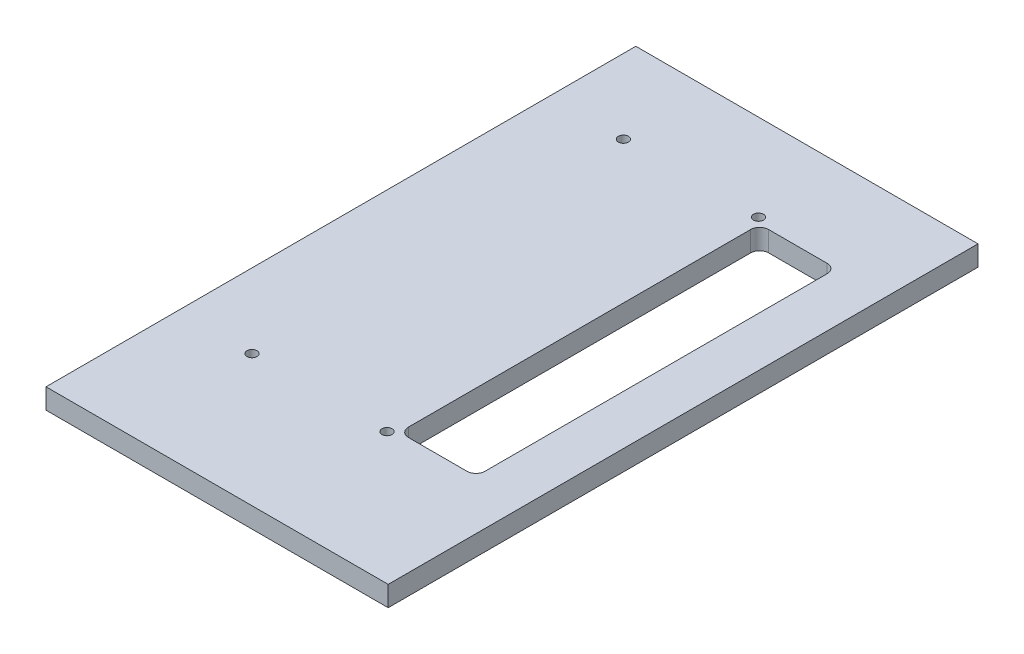
SolidWorks part; units mm, degrees
material "Poplar plywood painted"
ref_plane "Front Plane" through (0, 0, 0) normal (0, 0, 1) x (1, 0, 0)
ref_plane "Top Plane" through (0, 0, 0) normal (0, 1, 0) x (1, 0, 0)
ref_plane "Right Plane" through (0, 0, 0) normal (1, 0, 0) x (0, 0, -1)
sketch "Sketch1" plane through (0, 0, 0) normal (0, 1, 0) x (1, 0, 0)
  line L0 (-17, 80) -> (17, -80) construction
  line L1 (-113, 121) -> (39, 121)
  line L2 (-113, 121) -> (-113, -141)
  line L3 (-113, -141) -> (39, -141)
  line L4 (39, 121) -> (39, -141)
  line L5 (13, 80) -> (-13, 80)
  line L6 (17, 76) -> (17, -76)
  line L7 (13, -80) -> (-13, -80)
  line L8 (-17, 76) -> (-17, -76)
  arc A0 (-13, 80) -> (-17, 76) centre (-13, 76) ccw
  arc A1 (17, -76) -> (13, -80) centre (13, -76) cw
  arc A2 (-13, -80) -> (-17, -76) centre (-13, -76) cw
  arc A3 (13, 80) -> (17, 76) centre (13, 76) cw
  point P19 (17, 80)
  dimension "D7" = 4
  dimension "D1" = 34
  dimension "D2" = 160
  dimension "D3" = 39
  dimension "D4" = 113
  dimension "D5" = 121
  dimension "D6" = 141
extrude "Boss-Extrude1" add sketch "Sketch1" along normal blind 9
sketch "Sketch2" plane through (0, 0, 0) normal (0, -1, 0) x (1, 0, 0)
  line L0 (-80, 82.5) -> (-80, -82.5) construction
  line L1 (-80, -82.5) -> (-20, -82.5) construction
  line L2 (-20, -82.5) -> (-20, 82.5) construction
  line L3 (-20, 82.5) -> (-80, 82.5) construction
  line L5 (-20, 0) -> (0, 0) construction
  circle A0 centre (-20, 82.5) radius 2.25
  circle A1 centre (-80, 82.5) radius 2.25
  circle A2 centre (-20, -82.5) radius 2.25
  circle A3 centre (-80, -82.5) radius 2.25
  dimension "D1" = 20
  dimension "D2" = 4.5
  dimension "D3" = 60
  dimension "D4" = 165
extrude "Cut-Extrude1" cut sketch "Sketch2" against normal through all
sketch "Sketch3" plane through (0, 0, 0) normal (0, -1, 0) x (1, 0, 0)
  circle A0 centre (-80, 82.5) radius 4.5
  circle A1 centre (-20, 82.5) radius 4.5
  circle A2 centre (-20, -82.5) radius 4.5
  circle A3 centre (-80, -82.5) radius 4.5
  dimension "D1" = 9
extrude "Cut-Extrude2" cut sketch "Sketch3" against normal through all draft 45
